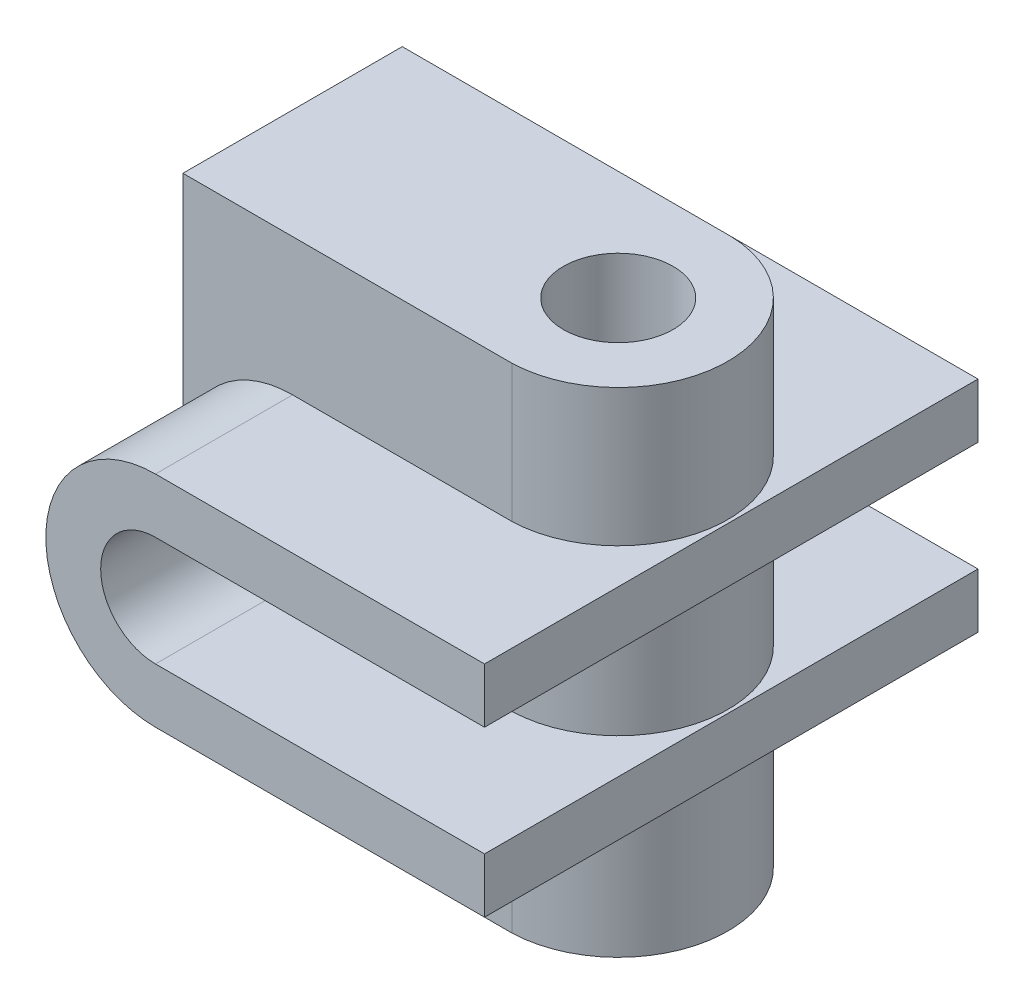
SolidWorks part; units mm, degrees
ref_plane "Спереди" through (0, 0, 0) normal (0, 0, 1) x (1, 0, 0)
ref_plane "Сверху" through (0, 0, 0) normal (0, 1, 0) x (1, 0, 0)
ref_plane "Справа" through (0, 0, 0) normal (1, 0, 0) x (0, 0, -1)
other "Configuration Table"
sketch "Эскиз1" plane through (0, 0, 0) normal (0, 0, 1) x (1, 0, 0)
  line L0 (0, -20) -> (60, -20)
  line L1 (0, 20) -> (60, 20)
  arc A0 (0, 20) -> (0, -20) centre (0, 0) ccw
extrude "Вытянуть-Тонкостенный1" add sketch "Эскиз1" along normal blind 90 separate body thin thin type one direction wall 10
sketch "Эскиз2" plane through (0, 0, 0) normal (0, 1, 0) x (1, 0, 0)
  line L0 (-20, -25) -> (-20, -65)
  line L1 (-20, 0) -> (-20, -90) construction
  line L2 (-20, -25) -> (40, -25)
  line L3 (-20, -65) -> (40, -65)
  arc A0 (40, -25) -> (40, -65) centre (39.3872, -45) cw
  circle A1 centre (39.3872, -45) radius 10
  dimension "D3" = 20
  dimension "D1" = 40
  dimension "D2" = 25
extrude "Бобышка-Вытянуть3" add sketch "Эскиз2" along normal blind 45 and the other way blind 45
